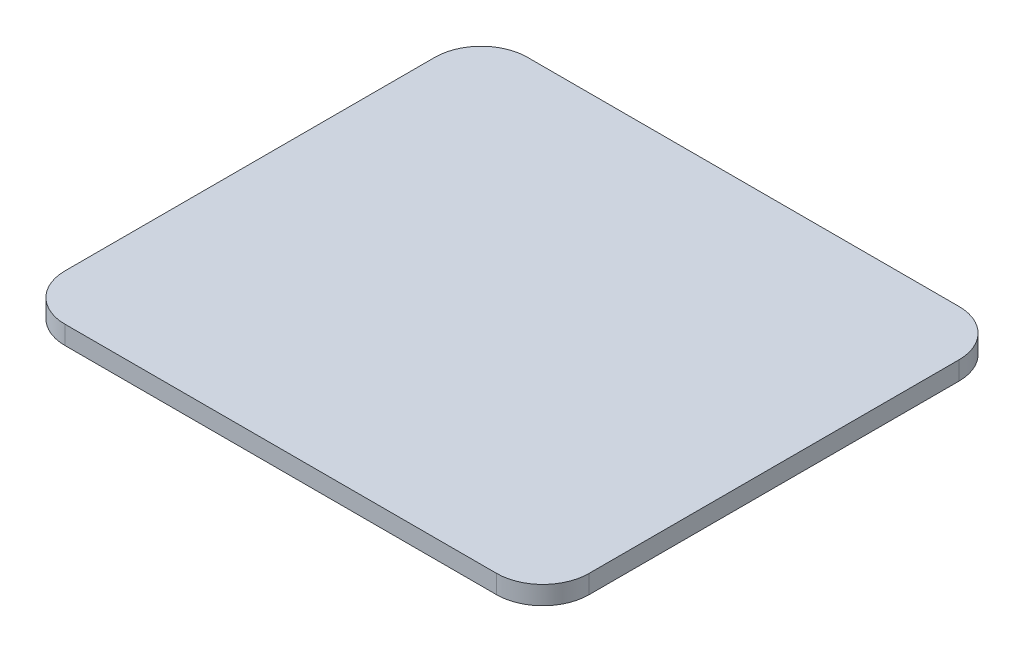
SolidWorks part; units mm, degrees
material "Acrílico (médio-alto impacto)"
ref_plane "Plano frontal" through (0, 0, 0) normal (0, 0, 1) x (1, 0, 0)
ref_plane "Plano superior" through (0, 0, 0) normal (0, 1, 0) x (1, 0, 0)
ref_plane "Plano direito" through (0, 0, 0) normal (1, 0, 0) x (0, 0, -1)
sketch "Esboço1" plane through (0, 0, 0) normal (0, 1, 0) x (1, 0, 0)
  line L1 (-170, -150) -> (170, -150)
  line L2 (-170, -150) -> (-170, 150)
  line L3 (-170, 150) -> (170, 150)
  line L4 (170, -150) -> (170, 150)
  line L5 (-170, -150) -> (170, 150) construction
  line L6 (-170, 150) -> (170, -150) construction
  point P0 (0, 0)
  dimension "D1" = 340
  dimension "D2" = 300
extrude "Ressalto-extrusão1" add sketch "Esboço1" along normal blind 12
fillet "Filete1" radius 30 4 edges at (-170, 6, -150) (170, 6, -150) (170, 6, 150) (-170, 6, 150)
